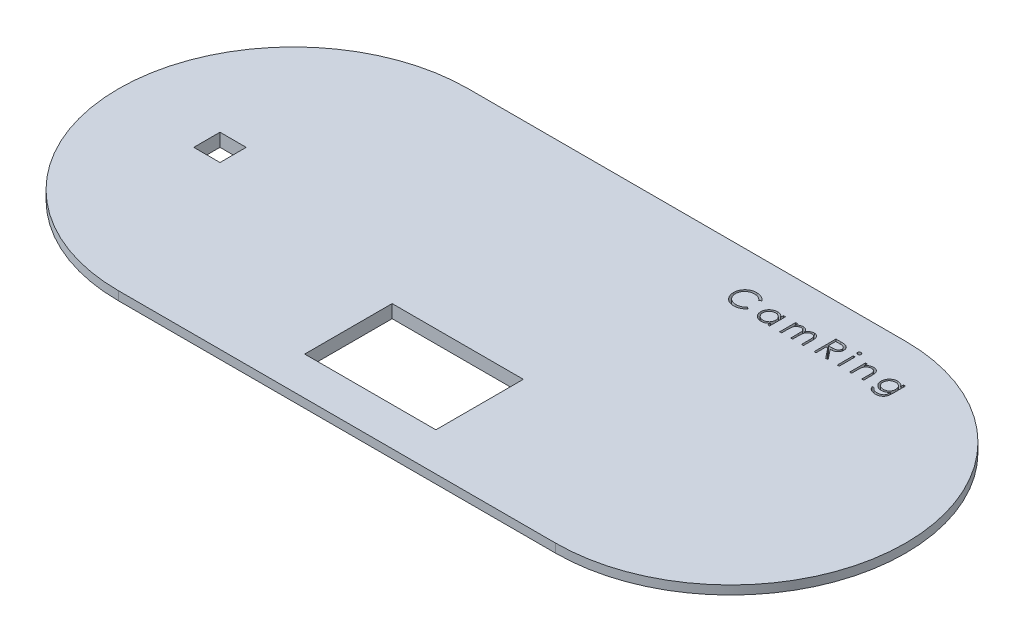
SolidWorks part; units mm, degrees
ref_plane "Front Plane" through (0, 0, 0) normal (0, 0, 1) x (1, 0, 0)
ref_plane "Top Plane" through (0, 0, 0) normal (0, 1, 0) x (1, 0, 0)
ref_plane "Right Plane" through (0, 0, 0) normal (1, 0, 0) x (0, 0, -1)
sketch "Croquis1" plane through (0, 0, 0) normal (0, 1, 0) x (1, 0, 0)
  line L0 (-48.8434, 0) -> (51.1566, 0) construction
  line L1 (-48.8434, 40) -> (51.1566, 40)
  line L2 (-48.8434, -40) -> (51.1566, -40)
  arc A0 (-48.8434, 40) -> (-48.8434, -40) centre (-48.8434, 0) ccw
  arc A1 (51.1566, -40) -> (51.1566, 40) centre (51.1566, 0) ccw
  point P3 (1.1566, 0)
  dimension "D2" = 80
  dimension "D1" = 100
extrude "Saliente-Extruir1" add sketch "Croquis1" along normal blind 2
sketch "Croquis2" plane through (0, 2, 0) normal (0, 1, 0) x (1, 0, 0)
  line L0 (-49.8434, 38) -> (50.1566, 38)
  line L1 (-49.8434, -38) -> (50.1566, -38)
  line L2 (51.1566, 40) -> (-48.8434, 40) construction
  line L3 (-48.8434, -40) -> (51.1566, -40) construction
  arc A0 (-49.8434, 38) -> (-49.8434, -38) centre (-49.8434, 0) ccw
  arc A1 (50.1566, 38) -> (50.1566, -38) centre (50.1566, 0) cw
  arc A2 (-48.8434, 40) -> (-48.8434, -40) centre (-48.8434, 0) ccw construction
  arc A3 (51.1566, -40) -> (51.1566, 40) centre (51.1566, 0) ccw construction
  dimension "D1" = 2
  dimension "D3" = 1
  dimension "D4" = 1
  dimension "D2" = 2
extrude "Saliente-Extruir3" add sketch "Croquis2" against normal blind 3
sketch "Croquis3" plane through (0, 2, 0) normal (0, 1, 0) x (1, 0, 0)
  line L0 (-96.3805, 0) -> (99.5575, 0) construction
  line L1 (0, 0) -> (0, -11.2525) construction
  line L2 (-15, -31.2525) -> (15, -31.2525)
  line L3 (-15, -31.2525) -> (-15, -11.2525)
  line L4 (-15, -11.2525) -> (15, -11.2525)
  line L5 (15, -31.2525) -> (15, -11.2525)
  line L6 (-15, -31.2525) -> (15, -11.2525) construction
  line L7 (-15, -11.2525) -> (15, -31.2525) construction
  point P3 (0, -21.2525)
  dimension "D1" = 20
  dimension "D2" = 30
extrude "Cortar-Extruir1" cut sketch "Croquis3" against normal blind 3
sketch "Croquis5" plane through (0, 2, 0) normal (0, 1, 0) x (1, 0, 0)
  line L1 (-68.6242, 3) -> (-62.6242, 3)
  line L2 (-68.6242, 3) -> (-68.6242, -3)
  line L3 (-68.6242, -3) -> (-62.6242, -3)
  line L4 (-62.6242, 3) -> (-62.6242, -3)
  line L5 (-68.6242, 3) -> (-62.6242, -3) construction
  line L6 (-68.6242, -3) -> (-62.6242, 3) construction
  point P0 (-65.6242, 0)
  dimension "D1" = 6
  dimension "D2" = 6
extrude "Cortar-Extruir2" cut sketch "Croquis5" against normal blind 3
sketch "Croquis6" plane through (0, 2, 0) normal (0, 1, 0) x (1, 0, 0)
  text T0 "CamRing" font "Century Gothic" height 5
extrude "Cortar-Extruir3" cut sketch "Croquis6" against normal blind 3
